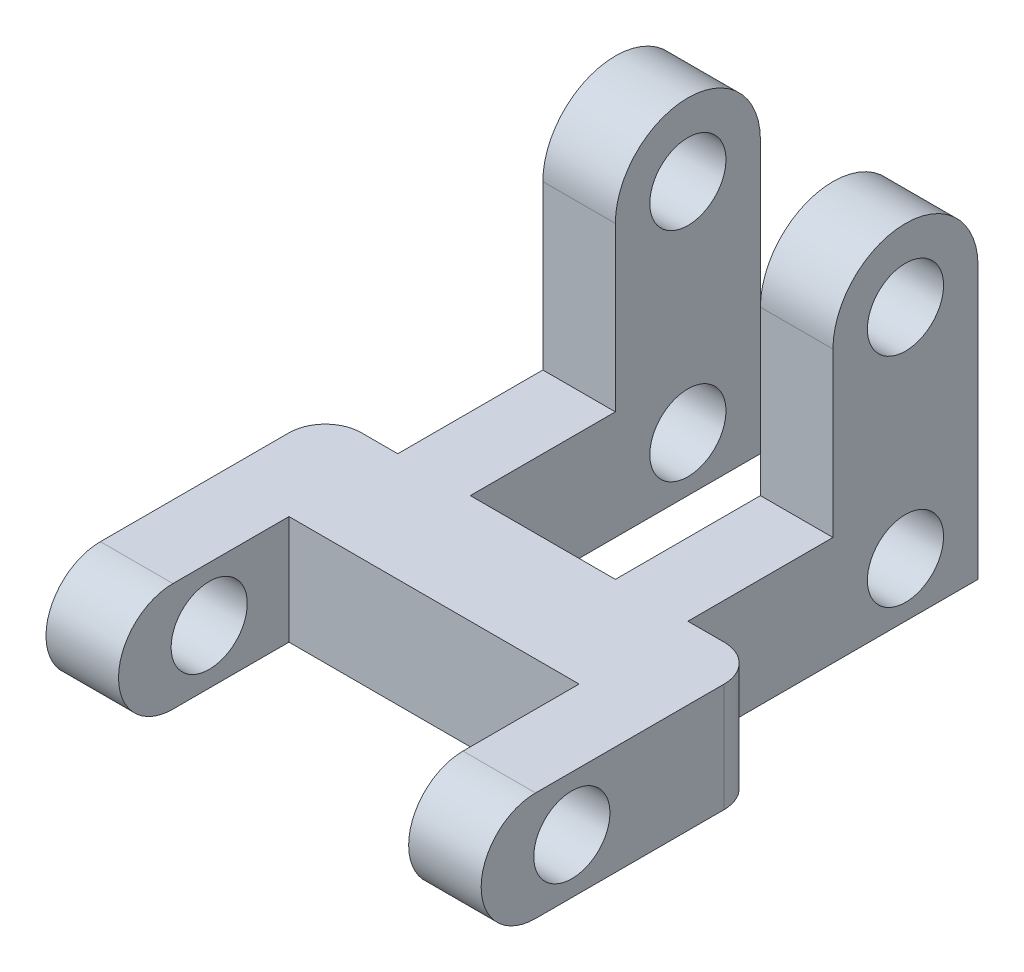
SolidWorks part; units mm, degrees
ref_plane "前视基准面" through (0, 0, 0) normal (0, 0, 1) x (1, 0, 0)
ref_plane "上视基准面" through (0, 0, 0) normal (0, 1, 0) x (1, 0, 0)
ref_plane "右视基准面" through (0, 0, 0) normal (1, 0, 0) x (0, 0, -1)
other "Configuration Table"
sketch "草图1" plane through (0, 0, 0) normal (0, 1, 0) x (1, 0, 0)
  line L0 (-6, 0) -> (6, 0)
  line L1 (-6, 0) -> (-6, -8.7)
  line L2 (-6, -8.7) -> (-4, -8.7)
  line L3 (-4, -8.7) -> (-4, -3)
  line L4 (-4, -3) -> (4, -3)
  line L5 (4, -3) -> (4, -8.7)
  line L6 (4, -8.7) -> (6, -8.7)
  line L7 (6, -8.7) -> (6, 0)
  point P4 (0, 0)
  dimension "D1" = 8.7
  dimension "D2" = 2
  dimension "D3" = 5.7
  dimension "D4" = 8
  dimension "D5" = 8.7
  dimension "D6" = 5.7
  dimension "D7" = 90
  dimension "D8" = 6
extrude "凸台-拉伸1" add sketch "草图1" along normal blind 3
sketch "草图2" plane through (-6, 0, 0) normal (-1, 0, 0) x (0, 0, 1)
  line L0 (0, 3) -> (8.7, 3) construction
  line L2 (6.2, 3) -> (0, 3)
  line L3 (0, 3) -> (0, 0)
  line L4 (0, 0) -> (6.2, 0)
  arc A0 (6.2, 0) -> (6.2, 3) centre (6.2, 1.5) ccw
  dimension "D2" = 1.5
  dimension "D1" = 6.2
  dimension "D3" = 6.2
  dimension "D4" = 1.5
extrude "切除-拉伸1" cut sketch "草图2" against normal blind 12 flip side to cut
sketch "草图3" plane through (-6, 0, 0) normal (-1, 0, 0) x (0, 0, 1)
  circle A2 centre (5.2, 1.5) radius 1.05
  dimension "D1" = 5.2
  dimension "D3" = 2.1
  dimension "D2" = 1.5
extrude "切除-拉伸2" cut sketch "草图3" against normal blind 12
fillet "圆角1" radius 1 2 edges at (6, 1.5, 0) (-6, 1.5, 0)
sketch "草图4" plane through (0, 0, 0) normal (0, 0, -1) x (-1, 0, 0)
  line L0 (0, 3) -> (0, 0) construction
  line L1 (-5, 3) -> (5, 3) construction
  circle A0 centre (0, 1.5) radius 0.95
  dimension "D1" = 1.9
extrude "凸台-拉伸2" add sketch "草图4" along normal blind 2
ref_plane "基准面1" through (0, 0, -2) normal (0, 0, -1) x (-1, 0, 0)
sketch "草图5" plane through (0, 0, -2) normal (0, 0, -1) x (-1, 0, 0)
  line L23 (-4, 3) -> (4, 3)
  line L24 (-5, 3) -> (5, 3) construction
  line L25 (4, 3) -> (4, 0)
  line L26 (-5, 0) -> (5, 0) construction
  line L27 (4, 0) -> (-4, 0)
  line L28 (-4, 0) -> (-4, 3)
  point P5 (0, 3)
  dimension "D1" = 90
  dimension "D2" = 3
extrude "凸台-拉伸3" add sketch "草图5" along normal blind 6
sketch "草图6" plane through (4, 0, 0) normal (1, 0, 0) x (0, 0, -1)
  line L0 (8, 1.5) -> (6, 1.5) construction
  line L1 (8, 3) -> (8, 0) construction
  circle A1 centre (6, 1.5) radius 1.05
  dimension "D3" = 2.1
  dimension "D1" = 2
extrude "切除-拉伸3" cut sketch "草图6" against normal blind 12
sketch "草图8" plane through (0, 3, 0) normal (0, 1, 0) x (1, 0, 0)
  line L0 (-1.5, 8) -> (1.5, 8)
  line L1 (-4, 8) -> (-2, 8) construction
  line L2 (1.5, 6) -> (-1.5, 6)
  line L11 (-1.5, 8) -> (-2, 8)
  line L13 (-2, 8) -> (-2, 6)
  line L14 (-2, 6) -> (-1.5, 6)
  line L15 (4, 8) -> (2, 8) construction
  line L16 (1.5, 8) -> (2, 8)
  line L17 (2, 8) -> (2, 6)
  line L18 (2, 6) -> (1.5, 6)
  line L19 (-4, 8) -> (4, 8) construction
  line L20 (4, 8) -> (4, 2) construction
  dimension "D1" = 2
  dimension "D2" = 2
  dimension "D3" = 3
  dimension "D4" = 6
  dimension "D5" = 1.5
  dimension "D6" = 3
  dimension "D7" = 1.5
extrude "切除-拉伸4" cut sketch "草图8" against normal blind 8
sketch "草图9" plane through (0, 3, 0) normal (0, 1, 0) x (1, 0, 0)
  line L7 (-3.5, 7) -> (-3.5, 10)
  line L8 (-3.5, 10) -> (-1.5, 10)
  line L9 (-1.5, 10) -> (-1.5, 7)
  line L10 (-1.5, 7) -> (-3.5, 7)
  dimension "D1" = 1.5
  dimension "D2" = 2
  dimension "D3" = 3
  dimension "D4" = 7
sketch "草图10" plane through (-4, 0, 0) normal (-1, 0, 0) x (0, 0, 1)
  line L0 (-8, 3) -> (-8, 7.5)
  line L3 (-8, 3) -> (-2, 3) construction
  line L5 (-8, 3) -> (-4, 3)
  line L6 (-8, 0) -> (-8, 3) construction
  line L7 (-4, 3) -> (-4, 7.5)
  line L8 (-8, 7.5) -> (-4, 7.5) construction
  arc A1 (-4, 7.5) -> (-8, 7.5) centre (-6, 7.5) ccw
  dimension "D2" = 4
  dimension "D1" = 4.5
extrude "凸台-拉伸5" add sketch "草图10" against normal blind 2
sketch "草图11" plane through (-2, 0, 0) normal (-1, 0, 0) x (0, 0, 1)
  line L0 (-10, 7.5) -> (-2, 7.5) construction
  line L1 (-6, 7.5) -> (-6, 0.1) construction
  line L2 (-8, 0) -> (-8, 7.5) construction
  line L4 (-8, 0) -> (-6, 0.1) construction
  line L5 (-8, 0) -> (-2, 0) construction
  circle A1 centre (-6, 7.5) radius 1.05
  arc A2 (-4, 7.5) -> (-8, 7.5) centre (-6, 7.5) ccw construction
  dimension "D1" = 2.1
  dimension "D2" = 7.4
mirror "镜向2" about plane through (0, 0, 0) normal (1, 0, 0) of "凸台-拉伸5"
sketch "草图13" plane through (0, 0, -2) normal (0, 0, 1) x (1, 0, 0)
  line L0 (-4, 0) -> (-4, 3)
  line L1 (-4, 3) -> (4, 3)
  line L2 (4, 3) -> (4, 0)
  line L3 (4, 0) -> (-4, 0)
  line L4 (-4, 0) -> (-4, 3) construction
  dimension "D1" = 4
extrude "凸台-拉伸8" add sketch "草图13" along normal up to surface (2 mm away) up to face at (0.95, 1.5, 0)
sketch "草图14" plane through (0, 3, 0) normal (0, 1, 0) x (1, 0, 0)
  line L0 (2, 6) -> (2, 0)
  line L1 (-2, 6) -> (-2, 0)
  line L2 (-2, 0) -> (2, 0)
  line L3 (-2, 6) -> (2, 6)
  dimension "D1" = 6
  dimension "D2" = 6
extrude "切除-拉伸5" cut sketch "草图14" against normal blind 10
extrude "切除-拉伸6" cut sketch "草图11" against normal through all both and the other way through all contours A1
